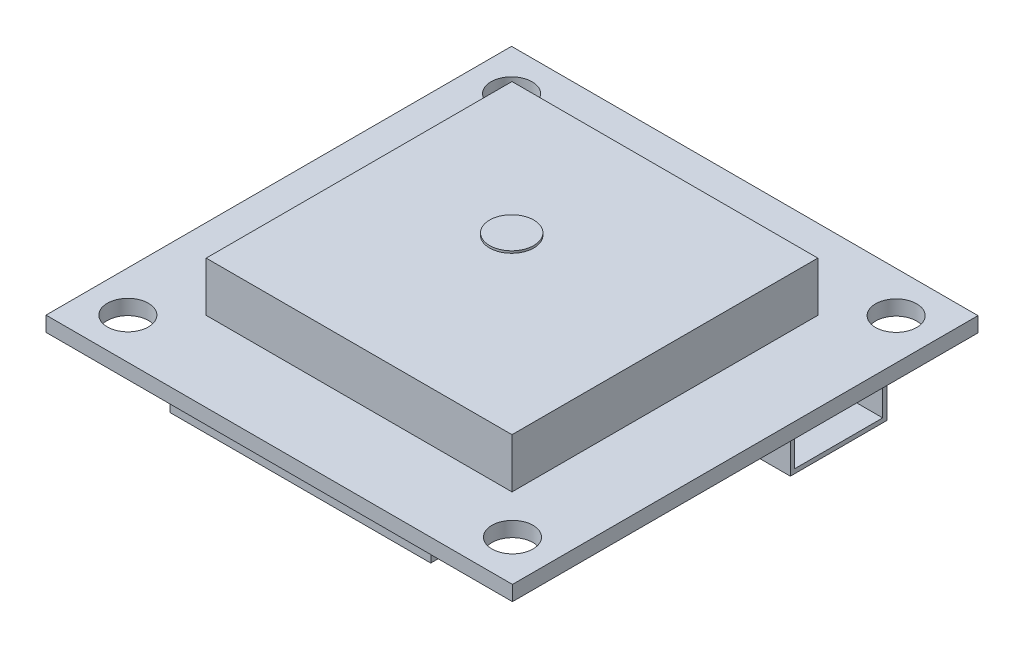
SolidWorks part; units mm, degrees
material "uBlox GPS"
ref_plane "Front Plane" through (0, 0, 0) normal (0, 0, 1) x (1, 0, 0)
ref_plane "Top Plane" through (0, 0, 0) normal (0, 1, 0) x (1, 0, 0)
ref_plane "Right Plane" through (0, 0, 0) normal (1, 0, 0) x (0, 0, -1)
sketch "Sketch1" plane through (0, 0, 0) normal (0, 1, 0) x (1, 0, 0)
  line L1 (0, 0) -> (38.354, 0)
  line L2 (0, 0) -> (0, 38.2778)
  line L3 (0, 38.2778) -> (38.354, 38.2778)
  line L4 (38.354, 0) -> (38.354, 38.2778)
  dimension "D1" = 38.2778
  dimension "D2" = 38.354
extrude "Board" add sketch "Sketch1" along normal blind 1.2319
sketch "Sketch3" plane through (0, 1.2319, 0) normal (0, 1, 0) x (1, 0, 0)
  line L0 (38.354, 19.1389) -> (31.75, 19.1389) construction
  line L1 (31.75, 31.7119) -> (6.604, 31.7119)
  line L2 (31.75, 31.7119) -> (31.75, 6.5659)
  line L3 (31.75, 6.5659) -> (6.604, 6.5659)
  line L4 (6.604, 31.7119) -> (6.604, 6.5659)
  line L5 (38.354, 0) -> (38.354, 38.2778) construction
  line L6 (19.177, 38.2778) -> (19.177, 31.7119) construction
  line L7 (38.354, 38.2778) -> (0, 38.2778) construction
  dimension "D1" = 25.146
  dimension "D2" = 25.146
extrude "GPS" add sketch "Sketch3" along normal blind 4.0767
sketch "Sketch5" plane through (0, 0, 0) normal (0, -1, 0) x (1, 0, 0)
  line L0 (38.354, 0) -> (38.354, -38.2778) construction
  line L1 (8.382, -1.8161) -> (29.8196, -1.8161)
  line L2 (8.382, -1.8161) -> (8.382, -18.6055)
  line L3 (8.382, -18.6055) -> (29.8196, -18.6055)
  line L4 (29.8196, -1.8161) -> (29.8196, -18.6055)
  line L5 (38.354, -38.2778) -> (0, -38.2778) construction
  dimension "D1" = 21.4376
  dimension "D2" = 16.7894
  dimension "D3" = 29.972
  dimension "D4" = 36.4617
extrude "uBlock chip" add sketch "Sketch5" along normal blind 2.4257
sketch "Sketch6" plane through (0, 0, 0) normal (0, -1, 0) x (-1, 0, 0)
  line L0 (-22.2758, 29.2481) -> (-18.8131, 29.2481) construction
  line L1 (-38.354, 38.2778) -> (0, 38.2778) construction
  line L2 (-18.8976, 32.6263) -> (-18.8976, 25.0521) construction
  line L3 (-38.354, 0) -> (-38.354, 38.2778) construction
  circle A0 centre (-22.2758, 32.6263) radius 3.3782
  dimension "D1" = 6.7564
  dimension "D2" = 9.0297
  dimension "D3" = 19.4564
extrude "Battery" add sketch "Sketch6" along normal blind 2.1082
sketch "Sketch7" plane through (0, 0, 0) normal (0, -1, 0) x (-1, 0, 0)
  line L0 (-38.354, 38.2778) -> (0, 38.2778) construction
  line L1 (-33.528, 23.3553) -> (-37.846, 23.3553)
  line L2 (-33.528, 23.3553) -> (-33.528, 31.3055)
  line L3 (-33.528, 31.3055) -> (-37.846, 31.3055)
  line L4 (-37.846, 23.3553) -> (-37.846, 31.3055)
  line L5 (-38.354, 0) -> (-38.354, 38.2778) construction
  dimension "D1" = 7.9502
  dimension "D2" = 4.318
  dimension "D3" = 14.9225
  dimension "D4" = 4.826
extrude "Connector" add sketch "Sketch7" along normal blind 2.9972
sketch "Sketch8" plane through (37.846, 0, 0) normal (1, 0, 0) x (0, 0, -1)
  line L0 (31.3055, 0) -> (23.3553, 0) construction
  line L1 (23.7109, -0.3556) -> (30.9499, -0.3556)
  line L2 (23.7109, -0.3556) -> (23.7109, -2.6416)
  line L3 (23.7109, -2.6416) -> (30.9499, -2.6416)
  line L4 (30.9499, -0.3556) -> (30.9499, -2.6416)
  line L5 (31.3055, -2.9972) -> (23.3553, -2.9972) construction
  line L6 (23.3553, -2.9972) -> (23.3553, 0) construction
  line L7 (31.3055, -2.9972) -> (31.3055, 0) construction
  dimension "D1" = 0.3556
  dimension "D2" = 0.3556
  dimension "D3" = 0.3556
  dimension "D4" = 0.3556
extrude "Cut-Extrude1" cut sketch "Sketch8" against normal blind 3.7592
sketch "Sketch9" plane through (0, 1.2319, 0) normal (0, 1, 0) x (1, 0, 0)
  line L0 (36.6776, 3.3655) -> (38.354, 3.3655) construction
  line L1 (34.9885, 1.6764) -> (34.9885, 0) construction
  line L2 (0, 0) -> (38.354, 0) construction
  line L3 (1.6764, 3.3655) -> (0, 3.3655) construction
  line L4 (38.354, 0) -> (38.354, 38.2778) construction
  line L5 (0, 38.2778) -> (0, 0) construction
  line L6 (34.9885, 36.6014) -> (34.9885, 38.2778) construction
  line L7 (38.354, 38.2778) -> (0, 38.2778) construction
  circle A0 centre (34.9885, 3.3655) radius 1.6891
  circle A1 centre (3.3655, 3.3655) radius 1.6891
  circle A2 centre (3.3655, 34.9123) radius 1.6891
  circle A3 centre (34.9885, 34.9123) radius 1.6891
  dimension "D1" = 3.3782
  dimension "D2" = 1.6764
extrude "Cut-Extrude2" cut sketch "Sketch9" against normal up to next
sketch "Sketch10" plane through (0, 5.3086, 0) normal (0, 1, 0) x (1, 0, 0)
  line L0 (17.5387, 22.5679) -> (22.9587, 22.5679) construction
  line L1 (15.7226, 20.7518) -> (15.7226, 15.1271) construction
  line L2 (6.604, 6.5659) -> (31.75, 6.5659) construction
  line L3 (31.75, 6.5659) -> (31.75, 31.7119) construction
  circle A0 centre (17.5387, 20.7518) radius 1.8161
  dimension "D1" = 3.6322
  dimension "D2" = 16.002
  dimension "D3" = 16.0274
extrude "Boss-Extrude6" add sketch "Sketch10" along normal blind 0.1778
sketch "Sketch11" plane through (0, 0, 0) normal (0, -1, 0) x (1, 0, 0)
  line L0 (7.8613, -7.466) -> (8.382, -7.466) construction
  line L1 (7.8613, -1.6446) -> (30.3403, -1.6446)
  line L2 (7.8613, -1.6446) -> (7.8613, -18.7769)
  line L3 (7.8613, -18.7769) -> (30.3403, -18.7769)
  line L4 (30.3403, -1.6446) -> (30.3403, -18.7769)
  line L5 (8.382, -1.8161) -> (8.382, -18.6055) construction
  line L6 (15.1347, -18.7769) -> (15.1347, -18.6055) construction
  line L7 (29.8196, -18.6055) -> (29.8196, -1.8161) construction
  line L8 (29.8196, -7.466) -> (30.3403, -7.466) construction
  line L9 (8.382, -18.6055) -> (29.8196, -18.6055) construction
  line L10 (14.874, -1.8161) -> (14.874, -1.6446) construction
  line L12 (29.8196, -1.8161) -> (8.382, -1.8161) construction
  dimension "D1" = 22.479
  dimension "D2" = 17.1323
extrude "Boss-Extrude7" add sketch "Sketch11" along normal blind 0.762
